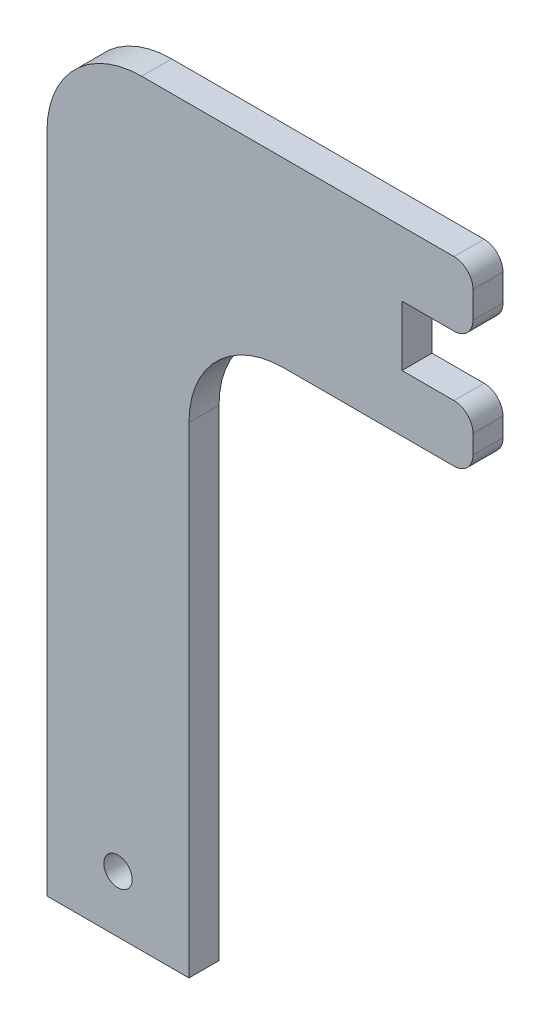
SolidWorks part; units mm, degrees
ref_plane "Front Plane" through (0, 0, 0) normal (0, 0, 1) x (1, 0, 0)
ref_plane "Top Plane" through (0, 0, 0) normal (0, 1, 0) x (1, 0, 0)
ref_plane "Right Plane" through (0, 0, 0) normal (1, 0, 0) x (0, 0, -1)
sketch "Sketch1" plane through (0, 0, 0) normal (0, 0, 1) x (1, 0, 0)
  line L1 (0, 0) -> (-45, 0)
  line L2 (0, 0) -> (0, -80)
  line L3 (0, -80) -> (-45, -80)
  line L4 (-45, 0) -> (-45, -80)
  dimension "D1" = 45
  dimension "D2" = 80
extrude "Boss-Extrude1" add sketch "Sketch1" along normal blind 3.175
sketch "Sketch2" plane through (0, 0, 3.175) normal (0, 0, 1) x (1, 0, 0)
  line L0 (0, -80) -> (0, 0) construction
  line L1 (-7.5, -6.825) -> (7.5, -6.825)
  line L2 (-7.5, -6.825) -> (-7.5, -13.175)
  line L3 (-7.5, -13.175) -> (7.5, -13.175)
  line L4 (7.5, -6.825) -> (7.5, -13.175)
  line L5 (-7.5, -6.825) -> (7.5, -13.175) construction
  line L6 (-7.5, -13.175) -> (7.5, -6.825) construction
  line L7 (0, 0) -> (-45, 0) construction
  point P0 (0, -10)
  dimension "D1" = 15
  dimension "D2" = 6.35
  dimension "D3" = 10
extrude "Cut-Extrude1" cut sketch "Sketch2" against normal through all
sketch "Sketch3" plane through (0, 0, 3.175) normal (0, 0, 1) x (1, 0, 0)
  line L0 (-7.5, -13.175) -> (0, -13.175) construction
  line L1 (0, -80) -> (-30, -80)
  line L2 (0, -80) -> (0, -19.175)
  line L3 (0, -19.175) -> (-30, -19.175)
  line L4 (-30, -80) -> (-30, -19.175)
  line L5 (-45, 0) -> (-45, -80) construction
  line L6 (-45, -80) -> (0, -80) construction
  circle A0 centre (-37.5, -74) radius 1.5
  dimension "D3" = 3
  dimension "D1" = 6
  dimension "D2" = 15
  dimension "D4" = 6
  dimension "D5" = 7.5
extrude "Cut-Extrude2" cut sketch "Sketch3" against normal through all
fillet "Fillet1" radius 10 2 edges at (-45, 0, 1.5875) (-30, -19.175, 1.5875)
fillet "Fillet2" radius 2 4 edges at (0, -19.175, 1.5875) (0, 0, 1.5875) (0, -13.175, 1.5875) (0, -6.825, 1.5875)
